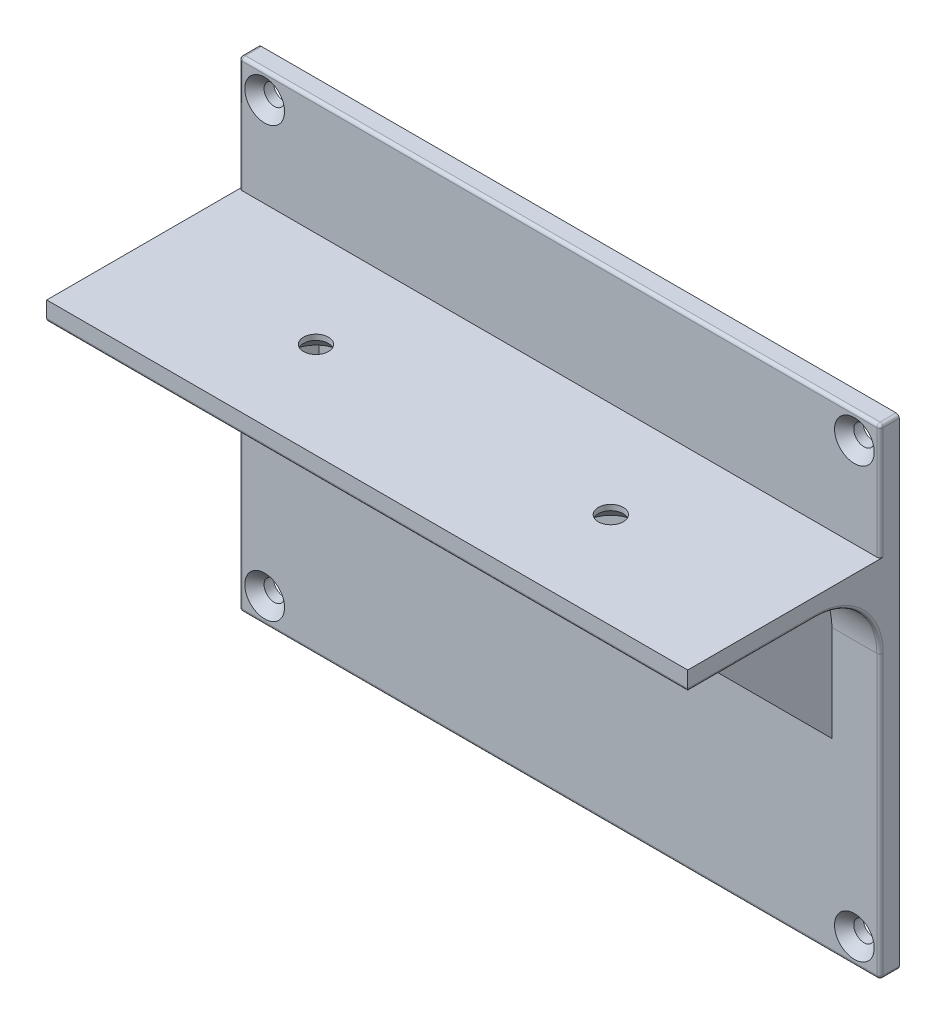
SolidWorks part; units mm, degrees
ref_plane "Płaszczyzna przednia" through (0, 0, 0) normal (0, 0, 1) x (1, 0, 0)
ref_plane "Płaszczyzna górna" through (0, 0, 0) normal (0, 1, 0) x (1, 0, 0)
ref_plane "Płaszczyzna prawa" through (0, 0, 0) normal (1, 0, 0) x (0, 0, -1)
sketch "Szkic1" plane through (0, 0, 0) normal (0, 0, 1) x (1, 0, 0)
  line L0 (-49.5, -49.8782) -> (49.5, -49.8782) construction
  line L1 (-50, 25.1218) -> (50, 25.1218)
  line L2 (-50, 25.1218) -> (-50, -49.8782)
  line L3 (-50, -49.8782) -> (50, -49.8782)
  line L4 (50, 25.1218) -> (50, -49.8782)
  line L5 (-50, 25.1218) -> (50, -49.8782) construction
  line L6 (-50, -49.8782) -> (50, 25.1218) construction
  line L7 (-49.5, -49.8782) -> (49.5, -49.8782) construction
  line L8 (50, -49.3782) -> (50, 24.6218) construction
  line L9 (50, -49.3782) -> (50, 24.6218) construction
  line L10 (-50, 24.6218) -> (-50, -49.3782) construction
  line L11 (-50, 24.6218) -> (-50, -49.3782) construction
  line L12 (49.5, 25.1218) -> (-49.5, 25.1218) construction
  line L13 (49.5, 25.1218) -> (-49.5, 25.1218) construction
extrude "Dodanie-wyciągnięcie1" add sketch "Szkic1" along normal blind 3
sketch "Szkic2" plane through (-50, 0, 0) normal (-1, 0, 0) x (0, 0, 1)
  line L0 (3, 7.1218) -> (33, 7.1218)
  line L1 (33, 7.1218) -> (33, 4.1218)
  line L2 (33, 4.1218) -> (3, 4.1218)
  line L3 (3, 25.1218) -> (3, -49.8782) construction
  line L4 (3, 4.1218) -> (3, 7.1218)
  line L5 (3, 25.1218) -> (0, 25.1218) construction
  point P9 (0, 0)
  dimension "D1" = 30
  dimension "D2" = 18
extrude "Dodanie-wyciągnięcie2" add sketch "Szkic2" against normal up to surface (100 mm away) up to face at (50, -12.3782, 1.5)
sketch "Szkic3" plane through (0, -12.3782, -40) normal (1, 0, 0) x (0, 0, -1)
  line L0 (-68, 16.5) -> (-43, -8.5)
  line L1 (-43, -37.5) -> (-43, 16.5) construction
  line L2 (-73, 16.5) -> (-43, 16.5) construction
  point P2 (0, 0)
  point P6 (0, 0)
  point P7 (0, 0)
  point P8 (-68.8212, 13.1143)
  point P9 (0, 0)
  dimension "D1" = 25
  dimension "D2" = 25
rib "Żebro6" sketch "Szkic3" sketch "Szkic3" thickness 5 extrusion direction parallel to sketch draft on no parameters "D1"=5
pattern_linear "Szyk liniowy1" count 2 spacing 40 along (-1, 0, 0) of "Żebro6"
pattern_linear "Szyk liniowy2" count 2 spacing 40 along (1, 0, 0) of "Żebro6"
sketch "Szkic4" plane through (0, 0, 3) normal (0, 0, 1) x (1, 0, 0)
  circle A0 centre (46, -45.8782) radius 2 construction
  circle A1 centre (-46, -45.8782) radius 2 construction
  circle A2 centre (46, 21.1218) radius 2 construction
  circle A3 centre (-46, 21.1218) radius 2 construction
  circle A4 centre (46, -45.8782) radius 2 construction
  circle A5 centre (-46, -45.8782) radius 2 construction
  circle A6 centre (46, 21.1218) radius 2 construction
  circle A7 centre (-46, 21.1218) radius 2 construction
  circle A8 centre (46, -45.8782) radius 1.6
  circle A9 centre (-46, -45.8782) radius 1.6
  circle A10 centre (46, 21.1218) radius 1.6
  circle A11 centre (-46, 21.1218) radius 1.6
  dimension "D1" = 3.2
extrude "Wytnij-wyciągnięcie1" cut sketch "Szkic4" against normal through all
chamfer "Sfazowanie1" distance 1.5 angle 45 4 edges at (47.6, -45.8782, 3) (-44.4, -45.8782, 3) (47.6, 21.1218, 3) (-44.4, 21.1218, 3)
hole_wizard "Pogłębienie stożkowe pod M3.5 wkręt do części metalowych z łbem soczewkowym1" positions "Szkic5" profile "Szkic7" countersink size "M3.5" standard "Ansi Metric" end condition through all
sketch "Szkic5" plane through (0, 4.1218, 0) normal (0, -1, 0) x (-1, 0, 0)
  line L0 (50, -3) -> (50, -33) construction
  line L1 (-50, -33) -> (-50, -3) construction
  point P0 (-23, -18)
  point P2 (23, -18)
  point P4 (0, 0)
  point P7 (50, -18)
  dimension "D1" = 27
  dimension "D2" = 27
sketch "Szkic7" plane through (23, 4.1218, 18) normal (1, 0, 0) x (0, 0, -1)
  line L0 (0, 0) -> (0, 21)
  line L1 (0, 21) -> (1.95, 21)
  line L2 (1.95, 21) -> (1.95, 2.15)
  line L3 (1.95, 2.15) -> (4.1, 0)
  line L5 (4.1, 0) -> (0, 0)
  line L6 (-1.95, 2.15) -> (-4.1, 0) construction
  line L11 (0, -6.35) -> (0, 107.95) construction
  dimension "Średnica otworu na wylot" = 3.9
  dimension "Głębokość otworu na wylot" = 21
  dimension "Średnica zewnętrznego pogłębienia stożkowego" = 8.2
  dimension "Kąt zewnętrznego pogłębienia stożkowego" = 90
fillet "Zaokrąglenie1" radius 10 4 edges at (46.25, 4.1218, 3) (20, 4.1218, 3) (-20, 4.1218, 3) (-46.25, 4.1218, 3)
fillet "Zaokrąglenie2" radius 0.5 15 edges at (50, 4.1218, 23) (50, 1.1929, 5.9289) (-50, 4.1218, 23) (-50, 1.1929, 5.9289) (0, 4.1218, 33) (50, 16.1218, 3) (50, -27.8782, 3) (0, 25.1218, 3) (-50, -27.8782, 3) (-50, 16.1218, 3) (0, -49.8782, 3) (50, -49.8782, 1.5) (-50, 25.1218, 1.5) (50, 25.1218, 1.5) (-50, -49.8782, 1.5)
equation "\"D2@Szkic5\"=\"D1@Szkic5\""
